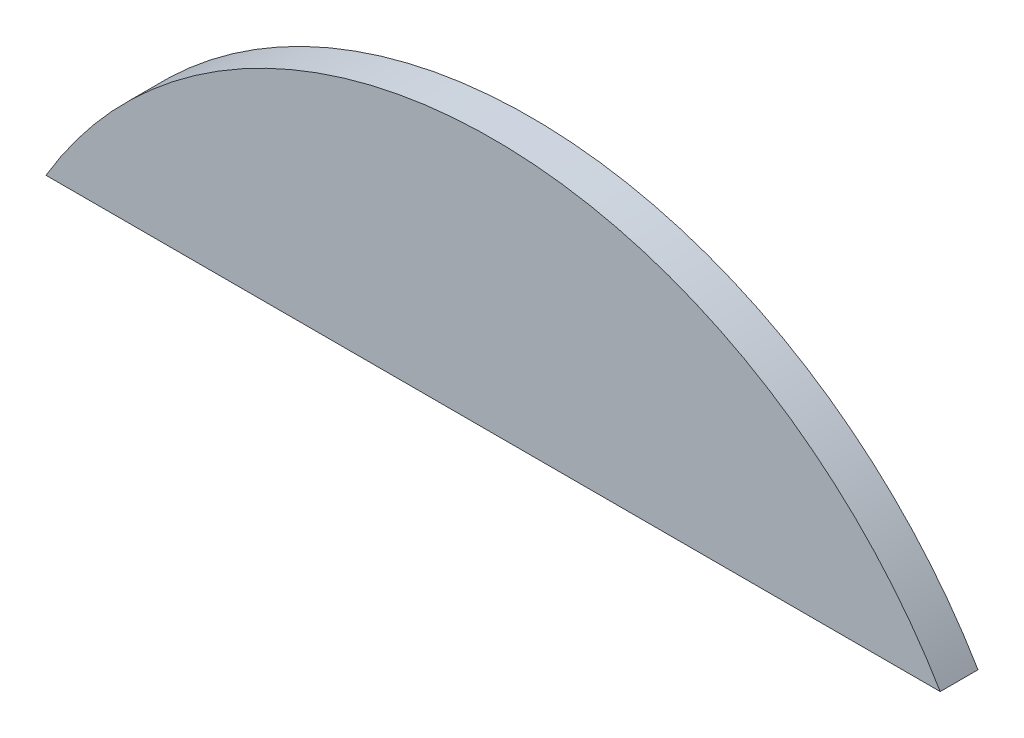
SolidWorks part; units mm, degrees
ref_plane "前视基准面" through (0, 0, 0) normal (0, 0, 1) x (1, 0, 0)
ref_plane "上视基准面" through (0, 0, 0) normal (0, 1, 0) x (1, 0, 0)
ref_plane "右视基准面" through (0, 0, 0) normal (1, 0, 0) x (0, 0, -1)
other "Configuration Table"
sketch "草图1" plane through (0, 0, 0) normal (0, 0, 1) x (1, 0, 0)
  line L0 (-23.6696, 14) -> (23.6696, 14)
  circle A0 centre (0, 0) radius 27.5 construction
  arc A1 (-23.6696, 14) -> (23.6696, 14) centre (0, 0) cw
  dimension "D1" = 55
  dimension "D2" = 14
extrude "凸台-拉伸1" add sketch "草图1" along normal blind 2
